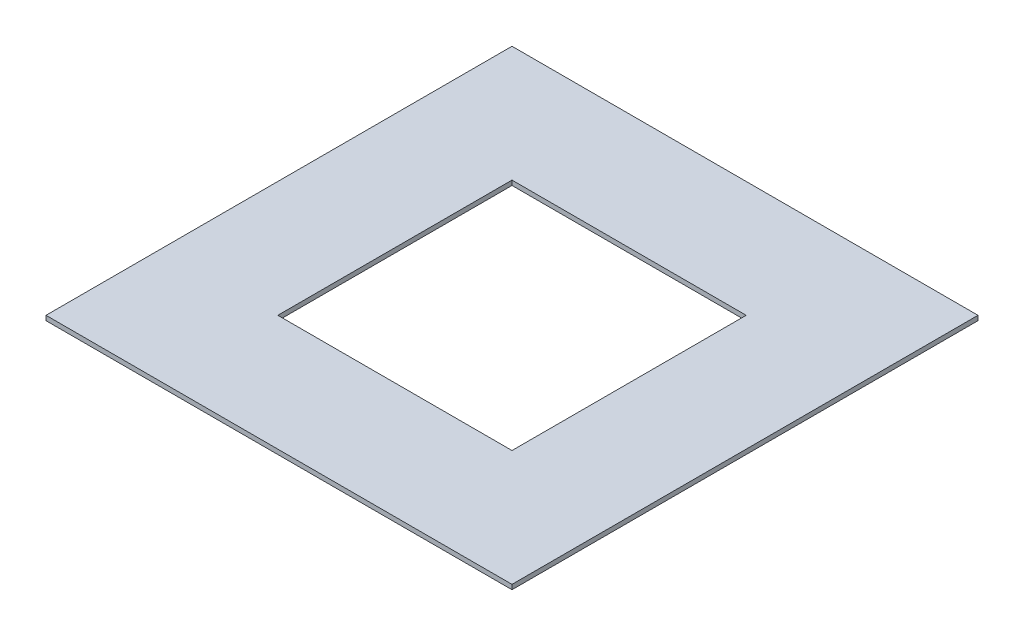
SolidWorks part; units mm, degrees
ref_plane "Alzado" through (0, 0, 0) normal (0, 0, 1) x (1, 0, 0)
ref_plane "Planta" through (0, 0, 0) normal (0, 1, 0) x (1, 0, 0)
ref_plane "Vista lateral" through (0, 0, 0) normal (1, 0, 0) x (0, 0, -1)
sketch "Croquis1" plane through (0, 0, 0) normal (0, 1, 0) x (1, 0, 0)
  line L1 (-49.75, 49.75) -> (49.75, 49.75)
  line L2 (-49.75, 49.75) -> (-49.75, -49.75)
  line L3 (-49.75, -49.75) -> (49.75, -49.75)
  line L4 (49.75, 49.75) -> (49.75, -49.75)
  line L5 (-49.75, 49.75) -> (49.75, -49.75) construction
  line L6 (-49.75, -49.75) -> (49.75, 49.75) construction
  line L7 (-25, 25) -> (25, 25)
  line L8 (-25, 25) -> (-25, -25)
  line L9 (-25, -25) -> (25, -25)
  line L10 (25, 25) -> (25, -25)
  line L11 (-25, 25) -> (25, -25) construction
  line L12 (-25, -25) -> (25, 25) construction
  point P0 (0, 0)
  point P5 (0, 0)
  dimension "D1" = 99.5
  dimension "D2" = 50
extrude "Saliente-Extruir1" add sketch "Croquis1" along normal blind 1
